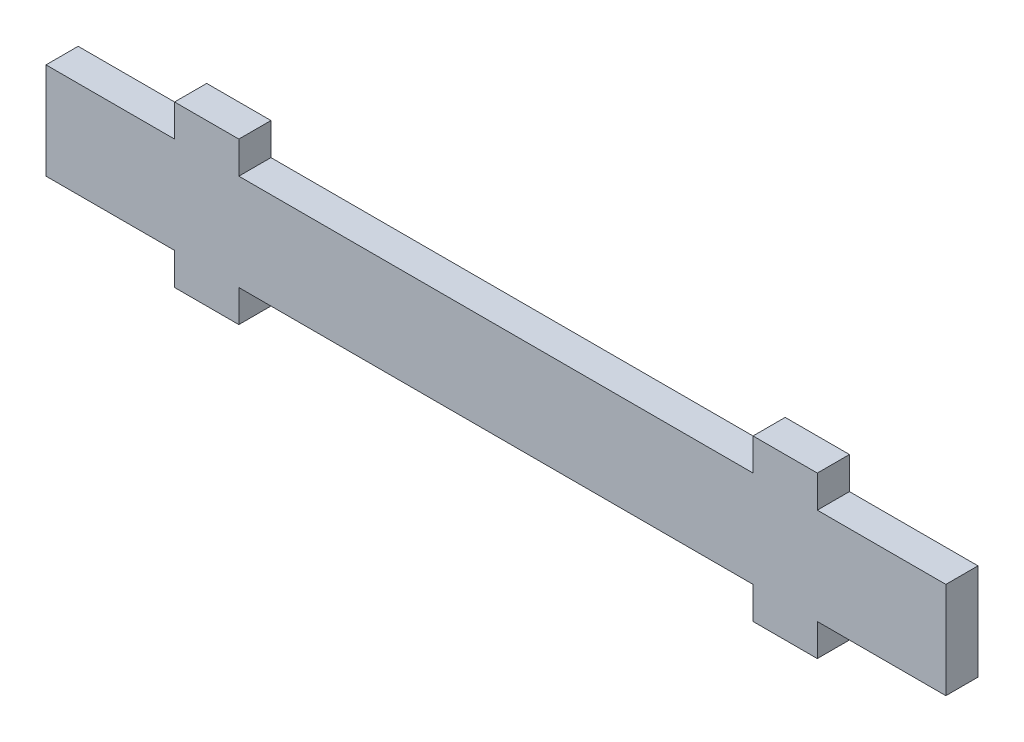
SolidWorks part; units mm, degrees
ref_plane "Front Plane" through (0, 0, 0) normal (0, 0, 1) x (1, 0, 0)
ref_plane "Top Plane" through (0, 0, 0) normal (0, 1, 0) x (1, 0, 0)
ref_plane "Right Plane" through (0, 0, 0) normal (1, 0, 0) x (0, 0, -1)
sketch "Sketch1" plane through (0, 0, 0) normal (0, 0, 1) x (1, 0, 0)
  line L1 (0, 0) -> (177.8, 0)
  line L2 (0, 0) -> (0, 19.05)
  line L3 (0, 19.05) -> (177.8, 19.05)
  line L4 (177.8, 0) -> (177.8, 19.05)
  dimension "D1" = 177.8
  dimension "D2" = 19.05
extrude "Boss-Extrude1" add sketch "Sketch1" along normal blind 6.35
sketch "Sketch2" plane through (0, 19.05, 0) normal (0, 1, 0) x (1, 0, 0)
  line L0 (177.8, 0) -> (0, 0) construction
  line L1 (25.4, 0) -> (38.1, 0)
  line L2 (25.4, 0) -> (25.4, -6.35)
  line L3 (25.4, -6.35) -> (38.1, -6.35)
  line L4 (38.1, 0) -> (38.1, -6.35)
  line L5 (177.8, -6.35) -> (0, -6.35) construction
  line L6 (0, -6.35) -> (0, 0) construction
  line L7 (139.7, 0) -> (152.4, 0)
  line L8 (139.7, 0) -> (139.7, -6.35)
  line L9 (139.7, -6.35) -> (152.4, -6.35)
  line L10 (152.4, 0) -> (152.4, -6.35)
  line L11 (177.8, -6.35) -> (177.8, 0) construction
  dimension "D1" = 12.7
  dimension "D2" = 12.7
  dimension "D3" = 25.4
  dimension "D4" = 25.4
extrude "Boss-Extrude2" add sketch "Sketch2" along normal blind 6.35
sketch "Sketch3" plane through (0, 0, 0) normal (0, -1, 0) x (1, 0, 0)
  line L0 (0, 6.35) -> (177.8, 6.35) construction
  line L1 (25.4, 6.35) -> (38.1, 6.35)
  line L2 (25.4, 6.35) -> (25.4, 0)
  line L3 (25.4, 0) -> (38.1, 0)
  line L4 (38.1, 6.35) -> (38.1, 0)
  line L5 (0, 0) -> (177.8, 0) construction
  line L6 (0, 6.35) -> (0, 0) construction
  line L7 (139.7, 6.35) -> (152.4, 6.35)
  line L8 (139.7, 6.35) -> (139.7, 0)
  line L9 (139.7, 0) -> (152.4, 0)
  line L10 (152.4, 6.35) -> (152.4, 0)
  line L11 (177.8, 6.35) -> (177.8, 0) construction
  point P15 (177.8, 3.175)
  dimension "D1" = 12.7
  dimension "D2" = 12.7
  dimension "D3" = 25.4
  dimension "D4" = 25.4
extrude "Boss-Extrude3" add sketch "Sketch3" along normal blind 6.35
